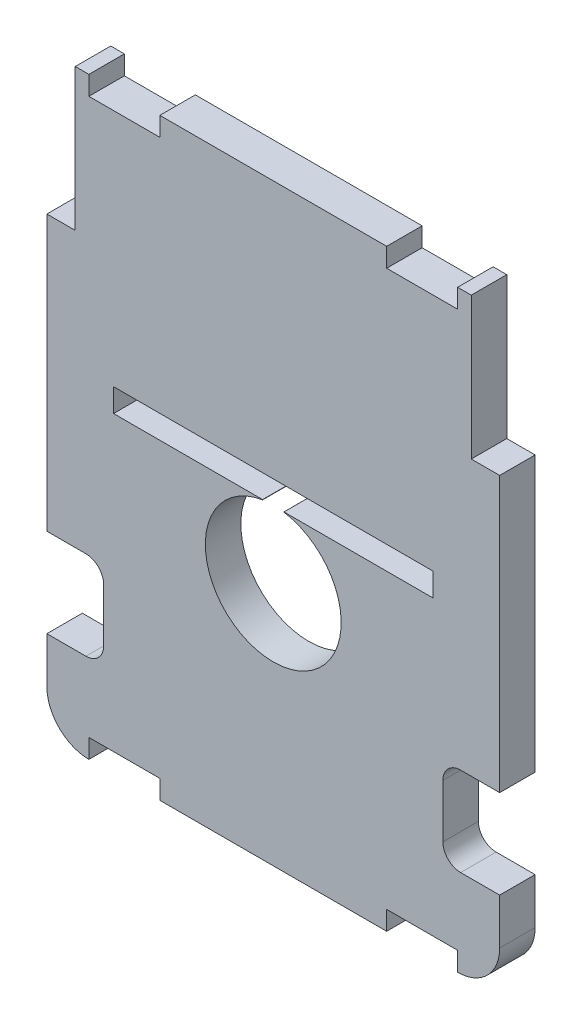
SolidWorks part; units mm, degrees
ref_plane "Front Plane" through (0, 0, 0) normal (0, 0, 1) x (1, 0, 0)
ref_plane "Top Plane" through (0, 0, 0) normal (0, 1, 0) x (1, 0, 0)
ref_plane "Right Plane" through (0, 0, 0) normal (1, 0, 0) x (0, 0, -1)
sketch "Sketch1" plane through (0, 0, 0) normal (0, 0, 1) x (1, 0, 0)
  line L0 (8823.0367, 3168.8375) -> (8823.0367, 3119.6758)
  line L1 (8823.0367, 3103.8008) -> (8823.0367, 3095.5966)
  line L2 (8762.2291, 3088.0782) -> (8802.8183, 3088.0782)
  line L3 (8742.0107, 3168.8375) -> (8742.0107, 3119.6758)
  line L4 (8742.0107, 3103.8008) -> (8742.0107, 3095.5966)
  line L5 (8817.9567, 3194.2375) -> (8815.5183, 3194.2375)
  line L6 (8802.8183, 3194.2375) -> (8762.2291, 3194.2375)
  line L7 (8749.5291, 3194.2375) -> (8747.0907, 3194.2375)
  line L8 (8780.6031, 3143.882) -> (8753.9487, 3143.882)
  line L9 (8811.0987, 3143.882) -> (8784.4444, 3143.882)
  line L10 (8811.0987, 3148.0476) -> (8811.0987, 3143.882)
  line L11 (8811.0987, 3148.0476) -> (8753.9487, 3148.0476)
  line L12 (8753.9487, 3148.0476) -> (8753.9487, 3143.882)
  line L13 (8817.9567, 3194.2375) -> (8817.9567, 3168.8375)
  line L14 (8817.9567, 3168.8375) -> (8823.0367, 3168.8375)
  line L15 (8747.0907, 3194.2375) -> (8747.0907, 3168.8375)
  line L16 (8747.0907, 3168.8375) -> (8742.0107, 3168.8375)
  line L17 (8823.0367, 3119.6758) -> (8816.0517, 3119.6758)
  line L18 (8823.0367, 3103.8008) -> (8816.0517, 3103.8008)
  line L19 (8812.8767, 3116.5008) -> (8812.8767, 3106.9758)
  line L20 (8742.0107, 3119.6758) -> (8748.9957, 3119.6758)
  line L21 (8742.0107, 3103.8008) -> (8748.9957, 3103.8008)
  line L22 (8752.1707, 3116.5008) -> (8752.1707, 3106.9758)
  line L23 (8749.5291, 3190.8339) -> (8762.2291, 3190.8339)
  line L24 (8802.8183, 3190.8339) -> (8815.5183, 3190.8339)
  line L25 (8749.5291, 3194.2375) -> (8749.5291, 3190.8339)
  line L26 (8762.2291, 3194.2375) -> (8762.2291, 3190.8339)
  line L27 (8815.5183, 3194.2375) -> (8815.5183, 3190.8339)
  line L28 (8802.8183, 3194.2375) -> (8802.8183, 3190.8339)
  line L29 (8815.5183, 3091.4818) -> (8802.8183, 3091.4818)
  line L30 (8762.2291, 3091.4818) -> (8749.5291, 3091.4818)
  line L31 (8749.5291, 3091.4818) -> (8749.5291, 3088.0782)
  line L32 (8762.2291, 3091.4818) -> (8762.2291, 3088.0782)
  line L33 (8815.5183, 3091.4818) -> (8815.5183, 3088.0782)
  line L34 (8802.8183, 3091.4818) -> (8802.8183, 3088.0782)
  arc A0 (8815.5183, 3088.0782) -> (8823.0367, 3095.5966) centre (8815.5183, 3095.5966) ccw
  arc A1 (8742.0107, 3095.5966) -> (8749.5291, 3088.0782) centre (8749.5291, 3095.5966) ccw
  arc A2 (8780.6071, 3143.8316) -> (8784.4404, 3143.8316) centre (8782.5237, 3131.8297) ccw
  arc A3 (8780.6071, 3143.8316) -> (8780.6031, 3143.882) centre (8780.6031, 3143.8566) ccw
  arc A4 (8784.4444, 3143.882) -> (8784.4404, 3143.8316) centre (8784.4444, 3143.8566) ccw
  arc A5 (8812.8767, 3106.9758) -> (8816.0517, 3103.8008) centre (8816.0517, 3106.9758) ccw
  arc A6 (8816.0517, 3119.6758) -> (8812.8767, 3116.5008) centre (8816.0517, 3116.5008) ccw
  arc A7 (8748.9957, 3103.8008) -> (8752.1707, 3106.9758) centre (8748.9957, 3106.9758) ccw
  arc A8 (8752.1707, 3116.5008) -> (8748.9957, 3119.6758) centre (8748.9957, 3116.5008) ccw
extrude "Boss-Extrude1" add sketch "Sketch1" along normal blind 6.35
